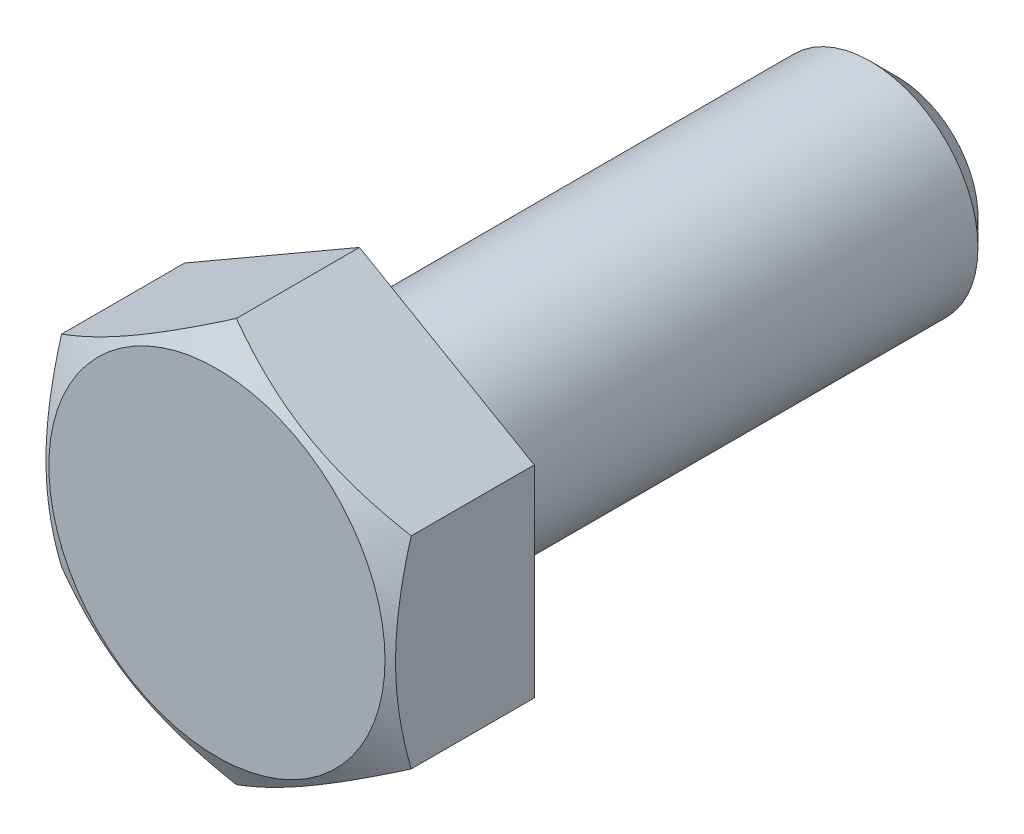
SolidWorks part; units mm, degrees
material "Обычная углеродистая сталь"
ref_plane "Спереди" through (0, 0, 0) normal (0, 0, 1) x (1, 0, 0)
ref_plane "Сверху" through (0, 0, 0) normal (0, 1, 0) x (1, 0, 0)
ref_plane "Справа" through (0, 0, 0) normal (1, 0, 0) x (0, 0, -1)
sketch "Эскиз1" plane through (0, 0, 0) normal (0, 0, 1) x (1, 0, 0)
  line L1 (0, 7.5056) -> (-6.5, 3.7528)
  line L2 (-6.5, 3.7528) -> (-6.5, -3.7528)
  line L3 (-6.5, -3.7528) -> (0, -7.5056)
  line L4 (0, -7.5056) -> (6.5, -3.7528)
  line L5 (6.5, -3.7528) -> (6.5, 3.7528)
  line L6 (6.5, 3.7528) -> (0, 7.5056)
  circle A0 centre (0, 0) radius 6.5 construction
  dimension "S" = 13
extrude "Бобышка-Вытянуть1" add sketch "Эскиз1" along normal blind 5.3
sketch "Эскиз2" plane through (0, 0, 5.3) normal (0, 0, 1) x (1, 0, 0)
  circle A0 centre (0, 0) radius 6.25
  dimension "D1" = 12.5
extrude "Вырез-Вытянуть1" cut sketch "Эскиз2" against normal through all draft 60 flip side to cut
sketch "Эскиз3" plane through (0, 0, 0) normal (0, 0, -1) x (-1, 0, 0)
  circle A0 centre (0, 0) radius 4
  dimension "d" = 8
extrude "Бобышка-Вытянуть2" add sketch "Эскиз3" along normal blind 20
cosmetic thread "Условное изображение резьбы1"
cosmetic thread "Условное изображение резьбы2" [suppressed]
cosmetic thread "Условное изображение резьбы3" [suppressed]
cosmetic thread "Условное изображение резьбы4" [suppressed]
cosmetic thread "Условное изображение резьбы5" [suppressed]
chamfer "Фаска1" distance 1 angle 45 1 edges at (-4, 0, -20)
